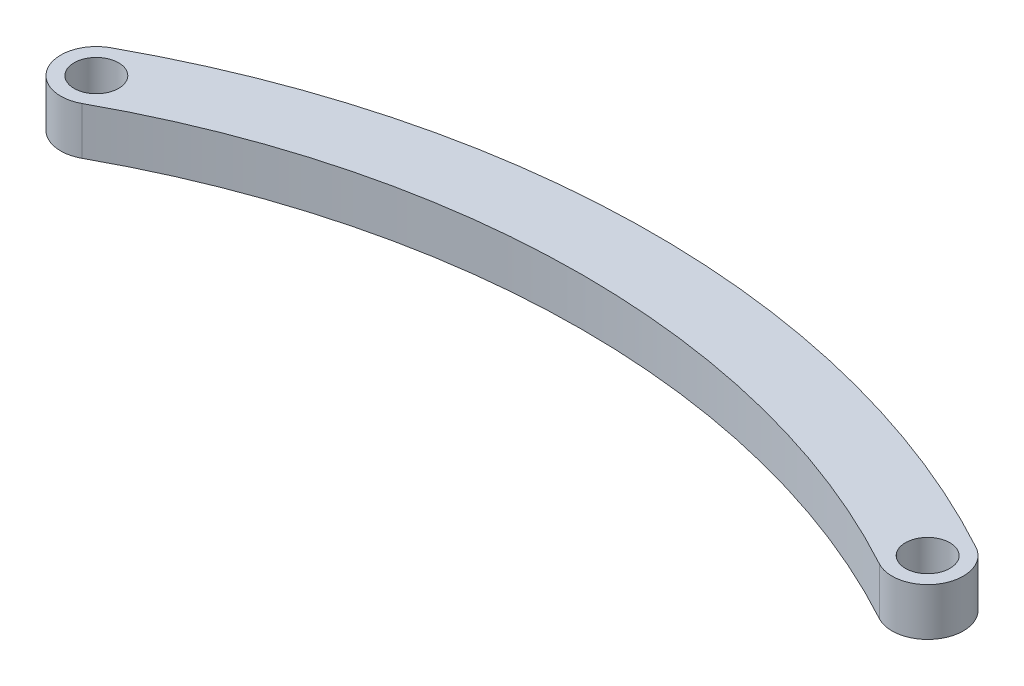
SolidWorks part; units mm, degrees
ref_plane "Front Plane" through (0, 0, 0) normal (0, 0, 1) x (1, 0, 0)
ref_plane "Top Plane" through (0, 0, 0) normal (0, 1, 0) x (1, 0, 0)
ref_plane "Right Plane" through (0, 0, 0) normal (1, 0, 0) x (0, 0, -1)
sketch "Esquisse1" plane through (0, 0, 0) normal (0, 1, 0) x (1, 0, 0)
  line L0 (-35, 0) -> (0, 0) construction
  line L1 (0, 0) -> (35, 0) construction
  circle A0 centre (-35, 0) radius 1.875
  circle A1 centre (35, 0) radius 1.875
  circle A2 centre (-35, 0) radius 3
  circle A3 centre (35, 0) radius 3
  circle A4 centre (0, -64.0625) radius 70
  circle A5 centre (0, -64.0625) radius 76
  dimension "D2" = 3.75
  dimension "D3" = 6
  dimension "D4" = 140
  dimension "D5" = 152
  dimension "D1" = 35
extrude "Boss.-Extru.1" add sketch "Esquisse1" along normal blind 4 contours A3 A5 A2 A4 | A2 A0 | A3 A1
